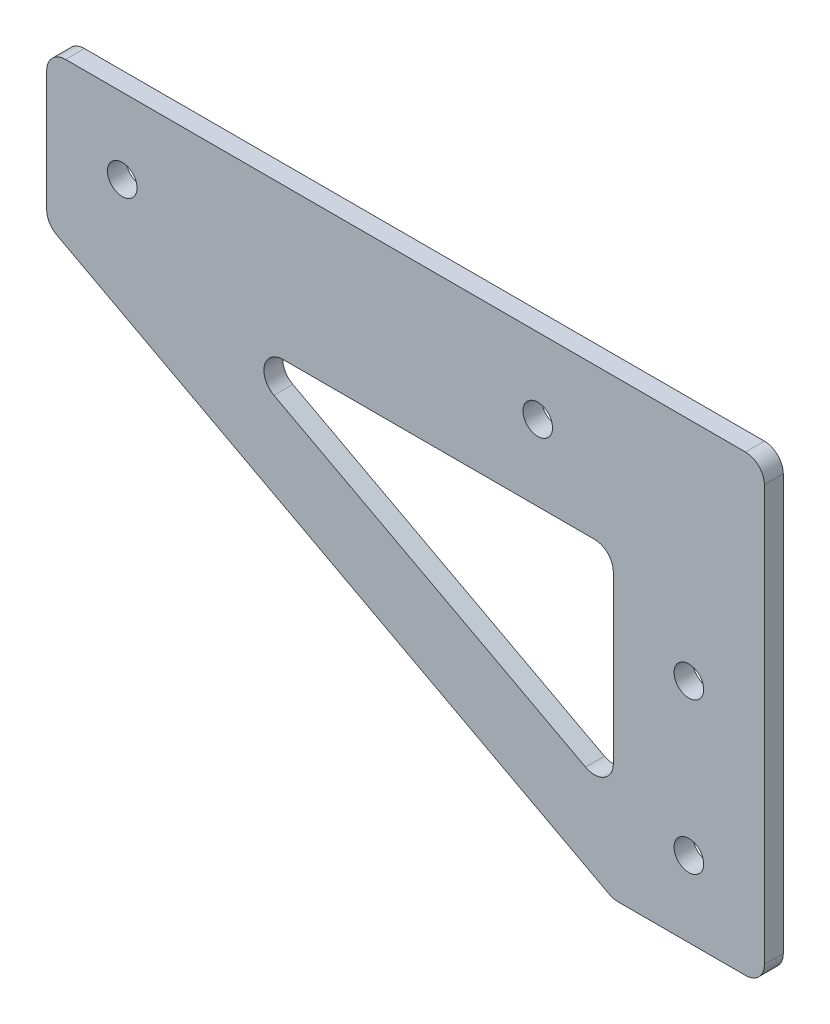
SolidWorks part; units mm, degrees
ref_plane "Front Plane" through (0, 0, 0) normal (0, 0, 1) x (1, 0, 0)
ref_plane "Top Plane" through (0, 0, 0) normal (0, 1, 0) x (1, 0, 0)
ref_plane "Right Plane" through (0, 0, 0) normal (1, 0, 0) x (0, 0, -1)
sketch "Sketch1" plane through (0, 0, 0) normal (0, 0, 1) x (1, 0, 0)
  line L0 (7.6272, 56.0268) -> (102.8772, 5.2268)
  line L1 (102.8772, 5.2268) -> (128.2772, 5.2268)
  line L2 (7.6272, 56.0268) -> (7.6272, 81.4268)
  line L3 (7.6272, 81.4268) -> (128.2772, 81.4268)
  line L4 (128.2772, 5.2268) -> (128.2772, 81.4268)
  line L5 (34.6147, 56.0268) -> (102.8772, 56.0268)
  line L6 (102.8772, 56.0268) -> (102.8772, 19.6202)
  line L7 (102.8772, 19.6202) -> (34.6147, 56.0268)
  point P4 (0, 0)
  dimension "D1" = 25.4
  dimension "D2" = 25.4
  dimension "D3" = 120.65
  dimension "D4" = 76.2
  dimension "D5" = 12.7
extrude "Boss-Extrude1" add sketch "Sketch1" along normal blind 3.175
sketch "Sketch2" plane through (0, 0, 3.175) normal (0, 0, 1) x (1, 0, 0)
  line L0 (102.8772, 56.0268) -> (34.6147, 56.0268) construction
  line L1 (128.2772, 5.2268) -> (128.2772, 81.4268) construction
  line L2 (128.2772, 81.4268) -> (7.6272, 81.4268) construction
  line L4 (102.8772, 5.2268) -> (128.2772, 5.2268) construction
  circle A0 centre (115.5772, 43.3268) radius 2.4892
  circle A1 centre (115.5772, 17.9268) radius 2.4892
  circle A2 centre (90.1772, 68.7268) radius 2.4892
  circle A3 centre (20.3272, 68.7268) radius 2.4892
  point P16 (115.5772, 13.2585)
  point P19 (0, 0)
  dimension "D1" = 69.85
  dimension "D5" = 12.7
  dimension "D6" = 4.9784
  dimension "D7" = 38.1
  dimension "D2" = 12.7
  dimension "D3" = 12.7
  dimension "D8" = 12.7
  dimension "D4" = 2
extrude "Cut-Extrude1" cut sketch "Sketch2" against normal through all
fillet "Fillet1" radius 3.175 8 edges at (128.2772, 81.4268, 1.5875) (128.2772, 5.2268, 1.5875) (102.8772, 5.2268, 1.5875) (102.8772, 19.6202, 1.5875) (102.8772, 56.0268, 1.5875) (34.6147, 56.0268, 1.5875) (7.6272, 56.0268, 1.5875) (7.6272, 81.4268, 1.5875)
